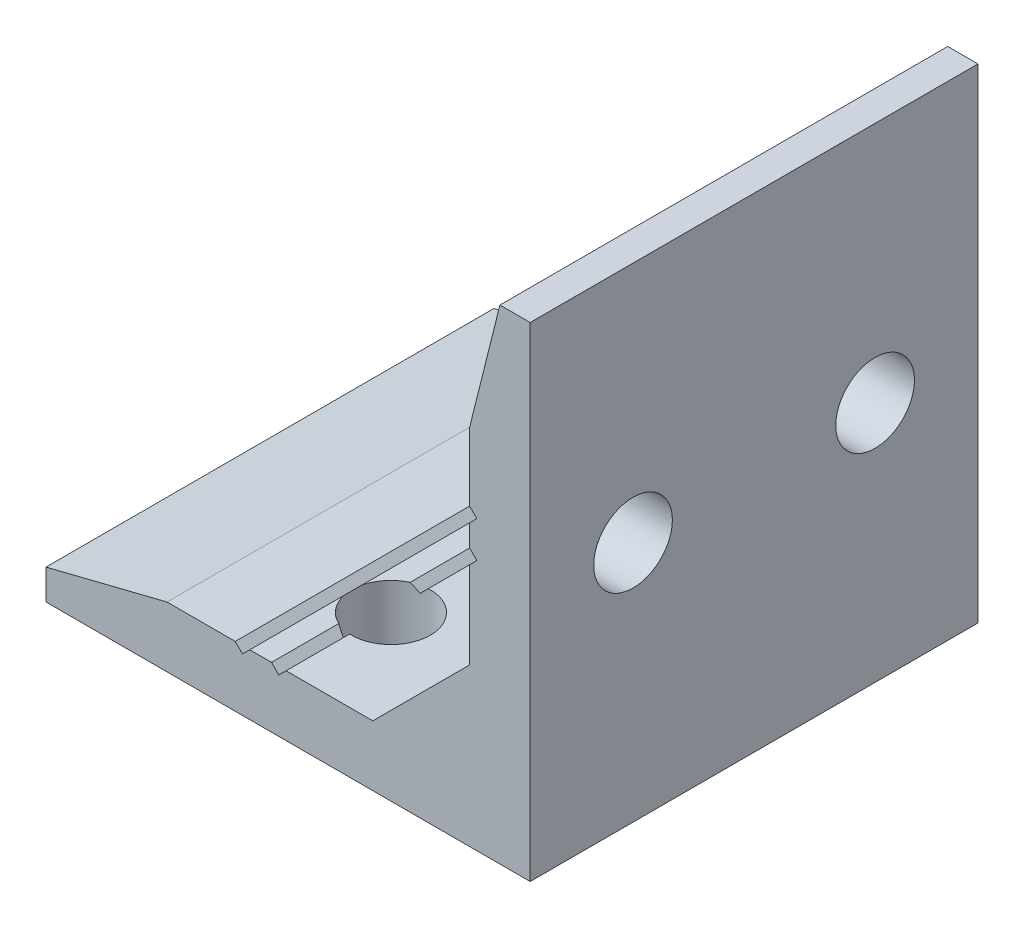
SolidWorks part; units mm, degrees
ref_plane "前视基准面" through (0, 0, 0) normal (0, 0, 1) x (1, 0, 0)
ref_plane "上视基准面" through (0, 0, 0) normal (0, 1, 0) x (1, 0, 0)
ref_plane "右视基准面" through (0, 0, 0) normal (1, 0, 0) x (0, 0, -1)
sketch "草图1" plane through (0, 0, 0) normal (0, 0, 1) x (1, 0, 0)
  line B0 (0, 0) -> (40, 0)
  line B1 (40, 0) -> (40, 40)
  line B2 (10, 5) -> (15.635, 5)
  line B3 (16.835, 5) -> (18.635, 5)
  line B4 (19.835, 5) -> (27, 5)
  line B5 (35, 13) -> (35, 20.165)
  line B6 (35, 21.365) -> (35, 23.165)
  line B7 (35, 24.365) -> (35, 30)
  line B8 (0, 2.5) -> (0, 0)
  line B9 (37.5, 40) -> (40, 40)
  line B10 (0, 2.5) -> (10, 5)
  line B11 (37.5, 40) -> (35, 30)
  line B12 (27, 5) -> (35, 13)
  line B13 (16.235, 4.4) -> (15.635, 5)
  line B14 (16.235, 4.4) -> (16.835, 5)
  line B15 (19.235, 4.4) -> (18.635, 5)
  line B16 (19.235, 4.4) -> (19.835, 5)
  line B17 (35.6, 23.765) -> (35, 24.365)
  line B18 (35.6, 23.765) -> (35, 23.165)
  line B19 (35.6, 20.765) -> (35, 21.365)
  line B20 (35.6, 20.765) -> (35, 20.165)
sketch_block_instance "A$C2EE5613F-1"
sketch_block "A$C2EE5613F"
extrude "凸台-拉伸1" add sketch "草图1" along normal mid plane 37
sketch "草图3" plane through (0, 5, 0) normal (0, 1, 0) x (1, 0, 0)
  line L0 (0, 0) -> (25.0328, 0) construction
  line L1 (0, -18.5) -> (0, 18.5) construction
  circle A0 centre (20, 10) radius 3.25
  circle A1 centre (20, -10) radius 3.25
  dimension "D1" = 10
  dimension "D2" = 20
extrude "切除-拉伸1" cut sketch "草图3" against normal through all
sketch "草图5" plane through (11, -11, 0) normal (-0.7071, 0.7071, 0) x (0, 0, 1)
  line L0 (-18.5, 28.2843) -> (18.5, 28.2843) construction
  line L1 (-18.5, 33.9411) -> (-18.5, 22.6274) construction
  line L2 (18.5, 33.9411) -> (18.5, 22.6274) construction
ref_plane "基准面2" through (20, 20, 0) normal (0.7071, 0.7071, 0) x (0.7071, -0.7071, 0)
mirror "镜向1" about plane through (20, 20, 0) normal (0.7071, 0.7071, 0) of "切除-拉伸1"
